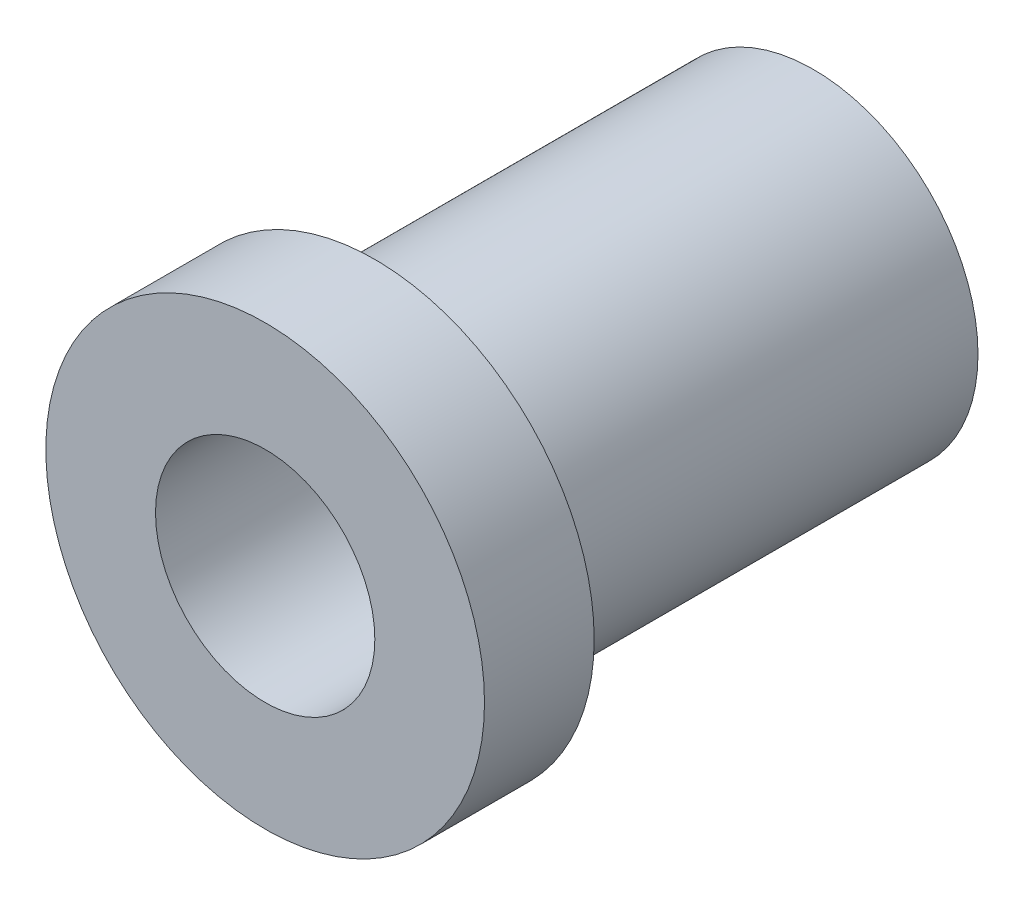
SolidWorks part; units mm, degrees
ref_plane "Front" through (0, 0, 0) normal (0, 0, 1) x (1, 0, 0)
ref_plane "Top" through (0, 0, 0) normal (0, 1, 0) x (1, 0, 0)
ref_plane "Right" through (0, 0, 0) normal (1, 0, 0) x (0, 0, -1)
sketch "Sketch1" plane through (0, 0, 0) normal (0, 0, 1) x (1, 0, 0)
  circle A0 centre (0, 0) radius 4
  dimension "D1" = 8
extrude "Boss-Extrude1" add sketch "Sketch1" along normal blind 2
sketch "Sketch2" plane through (0, 0, 0) normal (0, 0, 1) x (1, 0, 0)
  circle A0 centre (0, 0) radius 3
  dimension "D1" = 6
extrude "Boss-Extrude2" add sketch "Sketch2" against normal blind 8
sketch "Sketch3" plane through (0, 0, 2) normal (0, 0, 1) x (1, 0, 0)
  circle A0 centre (0, 0) radius 2
  dimension "D1" = 4
extrude "Cut-Extrude1" cut sketch "Sketch3" against normal blind 8
sketch "Panel Cut Guide" plane through (0, 0, 0) normal (0, 0, 1) x (1, 0, 0)
  circle A0 centre (0, 0) radius 3.05
  dimension "D1" = 6.1
